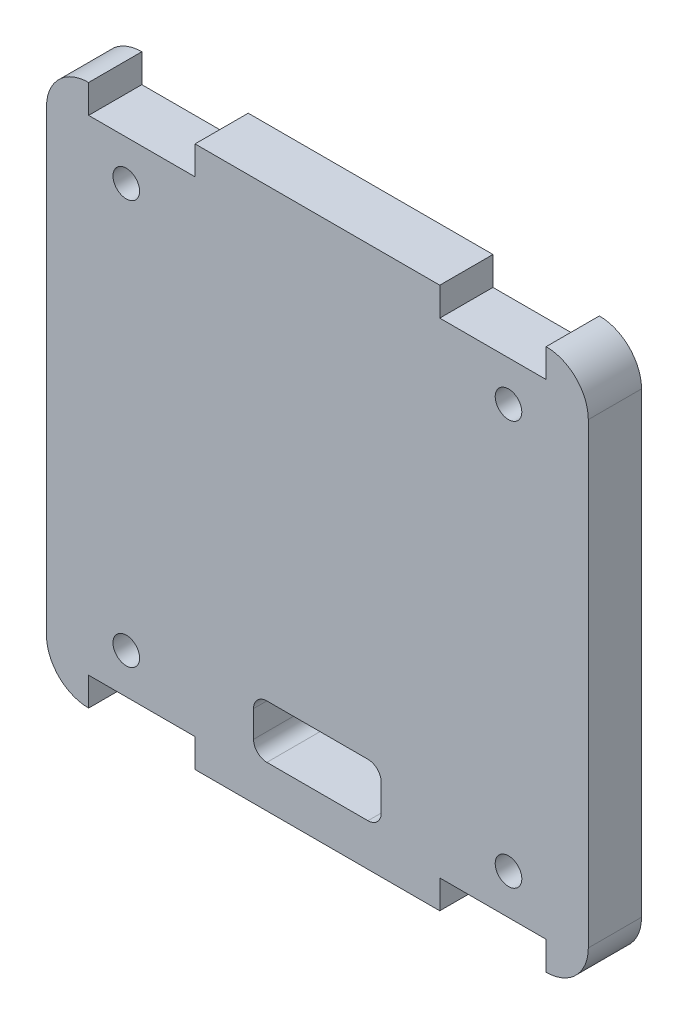
SolidWorks part; units mm, degrees
ref_plane "Front Plane" through (0, 0, 0) normal (0, 0, 1) x (1, 0, 0)
ref_plane "Top Plane" through (0, 0, 0) normal (0, 1, 0) x (1, 0, 0)
ref_plane "Right Plane" through (0, 0, 0) normal (1, 0, 0) x (0, 0, -1)
sketch "Sketch1" plane through (0, 0, 0) normal (0, 0, 1) x (1, 0, 0)
  line L0 (8672.4355, 2967.6949) -> (8672.4355, 2913.0849)
  line L1 (8654.7063, 2908.0557) -> (8625.4963, 2908.0557)
  line L2 (8667.4063, 2911.4593) -> (8654.7063, 2911.4593)
  line L3 (8625.4963, 2911.4593) -> (8612.7963, 2911.4593)
  line L4 (8607.7671, 2913.0849) -> (8607.7671, 2967.6949)
  line L5 (8625.4963, 2972.7241) -> (8654.7063, 2972.7241)
  line L6 (8612.7963, 2969.3205) -> (8625.4963, 2969.3205)
  line L7 (8654.7063, 2969.3205) -> (8667.4063, 2969.3205)
  line L8 (8612.7963, 2911.4593) -> (8612.7963, 2908.0557)
  line L9 (8625.4963, 2911.4593) -> (8625.4963, 2908.0557)
  line L10 (8667.4063, 2911.4593) -> (8667.4063, 2908.0557)
  line L11 (8654.7063, 2911.4593) -> (8654.7063, 2908.0557)
  line L12 (8667.4063, 2969.3205) -> (8667.4063, 2972.7241)
  line L13 (8654.7063, 2969.3205) -> (8654.7063, 2972.7241)
  line L14 (8612.7963, 2969.3205) -> (8612.7963, 2972.7241)
  line L15 (8625.4963, 2969.3205) -> (8625.4963, 2972.7241)
  line L16 (8634.0688, 2913.0849) -> (8646.1338, 2913.0849)
  line L17 (8647.7213, 2914.6724) -> (8647.7213, 2917.8474)
  line L18 (8646.1338, 2919.4349) -> (8634.0688, 2919.4349)
  line L19 (8632.4813, 2917.8474) -> (8632.4813, 2914.6724)
  arc A0 (8672.4355, 2967.6949) -> (8667.4063, 2972.7241) centre (8667.4063, 2967.6949) ccw
  arc A1 (8667.4063, 2908.0557) -> (8672.4355, 2913.0849) centre (8667.4063, 2913.0849) ccw
  arc A2 (8607.7671, 2913.0849) -> (8612.7963, 2908.0557) centre (8612.7963, 2913.0849) ccw
  arc A3 (8612.7963, 2972.7241) -> (8607.7671, 2967.6949) centre (8612.7963, 2967.6949) ccw
  circle A4 centre (8662.9105, 2964.5199) radius 1.5875
  circle A5 centre (8662.9105, 2916.2599) radius 1.5875
  circle A6 centre (8617.2921, 2964.5199) radius 1.5875
  circle A7 centre (8617.2921, 2916.2599) radius 1.5875
  arc A8 (8646.1338, 2913.0849) -> (8647.7213, 2914.6724) centre (8646.1338, 2914.6724) ccw
  arc A9 (8647.7213, 2917.8474) -> (8646.1338, 2919.4349) centre (8646.1338, 2917.8474) ccw
  arc A10 (8632.4813, 2914.6724) -> (8634.0688, 2913.0849) centre (8634.0688, 2914.6724) ccw
  arc A11 (8634.0688, 2919.4349) -> (8632.4813, 2917.8474) centre (8634.0688, 2917.8474) ccw
extrude "Boss-Extrude1" add sketch "Sketch1" along normal blind 6.35
